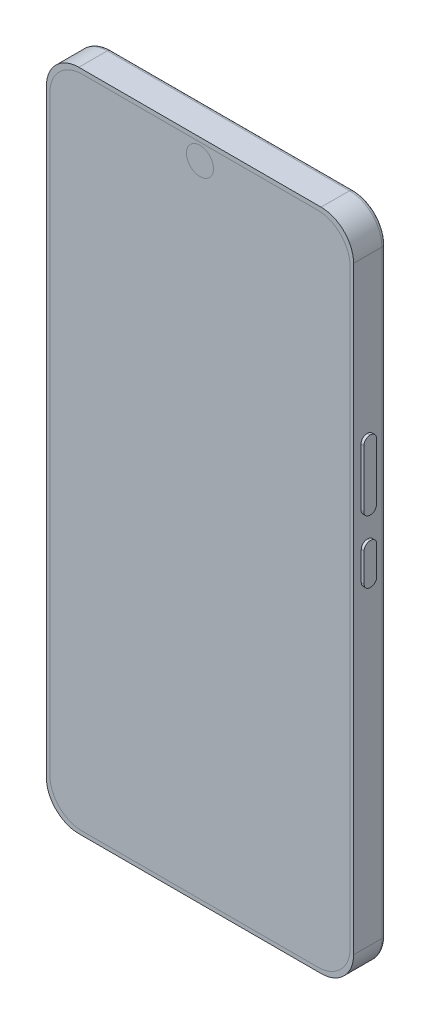
SolidWorks part; units mm, degrees
ref_plane "前视基准面" through (0, 0, 0) normal (0, 0, 1) x (1, 0, 0)
ref_plane "上视基准面" through (0, 0, 0) normal (0, 1, 0) x (1, 0, 0)
ref_plane "右视基准面" through (0, 0, 0) normal (1, 0, 0) x (0, 0, -1)
other "Configuration Table"
sketch "草图1" plane through (0, 0, 0) normal (0, 0, 1) x (1, 0, 0)
  line L1 (-62.3483, 120.7057) -> (-2.6683, 120.7057)
  line L2 (-70.3483, 112.7057) -> (-70.3483, -34.8243)
  line L3 (-62.3483, -42.8243) -> (-2.6683, -42.8243)
  line L4 (5.3317, 112.7057) -> (5.3317, -34.8243)
  arc A0 (-70.3483, -34.8243) -> (-62.3483, -42.8243) centre (-62.3483, -34.8243) ccw
  arc A1 (-2.6683, -42.8243) -> (5.3317, -34.8243) centre (-2.6683, -34.8243) ccw
  arc A2 (-2.6683, 120.7057) -> (5.3317, 112.7057) centre (-2.6683, 112.7057) cw
  arc A3 (-62.3483, 120.7057) -> (-70.3483, 112.7057) centre (-62.3483, 112.7057) ccw
  dimension "D1" = 8
extrude "凸台-拉伸2" add sketch "草图1" along normal blind 7.99
fillet "圆角4" radius 1 8 edges at (-32.5083, -42.8243, 0) (2.9886, -40.4812, 0) (5.3317, 38.9407, 0) (2.9886, 118.3625, 0) (-32.5083, 120.7057, 0) (-68.0052, 118.3625, 0) (-70.3483, 38.9407, 0) (-68.0052, -40.4812, 0)
sketch "草图2" plane through (0, 0, 7.99) normal (0, 0, 1) x (1, 0, 0)
  line L1 (-61.5125, 119.6413) -> (-3.5125, 119.6413)
  line L2 (-69.5125, 111.6413) -> (-69.5125, -33.8587)
  line L3 (-61.5125, -41.8587) -> (-3.5125, -41.8587)
  line L4 (4.4875, 111.6413) -> (4.4875, -33.8587)
  arc A0 (-69.5125, -33.8587) -> (-61.5125, -41.8587) centre (-61.5125, -33.8587) ccw
  arc A1 (-3.5125, -41.8587) -> (4.4875, -33.8587) centre (-3.5125, -33.8587) ccw
  arc A2 (-3.5125, 119.6413) -> (4.4875, 111.6413) centre (-3.5125, 111.6413) cw
  arc A3 (-61.5125, 119.6413) -> (-69.5125, 111.6413) centre (-61.5125, 111.6413) ccw
  circle A4 centre (-32.5125, 115.6413) radius 3.336
  dimension "D1" = 8
split line "分割线2"
sketch "草图6" plane through (0, 0, 0) normal (0, 0, -1) x (-1, 0, 0)
  line L0 (23.2504, 119.7057) -> (23.2504, -42.8243)
  line L1 (62.3483, 119.7057) -> (2.6683, 119.7057) construction
  line L2 (62.3483, -42.8243) -> (2.6683, -42.8243) construction
split line "分割线3"
sketch "草图7" plane through (5.3317, -15.0496, 0) normal (1, 0, 0) x (0, 0, -1)
  line L0 (-4.598, 67.2454) -> (-4.4802, 67.2454)
  line L1 (-4.6532, 89.7825) -> (-4.5354, 89.7825)
  line L2 (-6.1532, 88.2825) -> (-6.1532, 74.219)
  line L3 (-4.6532, 72.719) -> (-4.5354, 72.719)
  line L4 (-3.0354, 88.2825) -> (-3.0354, 74.219)
  line L5 (-6.098, 65.7454) -> (-6.098, 58.7454)
  line L6 (-4.598, 57.2454) -> (-4.4802, 57.2454)
  line L7 (-2.9802, 65.7454) -> (-2.9802, 58.7454)
  arc A0 (-4.5354, 72.719) -> (-3.0354, 74.219) centre (-4.5354, 74.219) ccw
  arc A1 (-6.1532, 74.219) -> (-4.6532, 72.719) centre (-4.6532, 74.219) ccw
  arc A2 (-4.5354, 89.7825) -> (-3.0354, 88.2825) centre (-4.5354, 88.2825) cw
  arc A3 (-4.6532, 89.7825) -> (-6.1532, 88.2825) centre (-4.6532, 88.2825) ccw
  arc A4 (-4.4802, 57.2454) -> (-2.9802, 58.7454) centre (-4.4802, 58.7454) ccw
  arc A5 (-6.098, 58.7454) -> (-4.598, 57.2454) centre (-4.598, 58.7454) ccw
  arc A6 (-4.4802, 67.2454) -> (-2.9802, 65.7454) centre (-4.4802, 65.7454) cw
  arc A7 (-4.598, 67.2454) -> (-6.098, 65.7454) centre (-4.598, 65.7454) ccw
  dimension "D1" = 1.5
extrude "凸台-拉伸4" add sketch "草图7" along normal blind 0.7 contours L2 A1 L3 A0 L4 A2 L1 A3 | L0 A6 L7 A4 L6 A5 L5 A7
sketch "草图8" plane through (0, -42.8243, 0) normal (0, -1, 0) x (1, 0, 0)
  line L1 (-59.1647, 6.3345) -> (-49.1647, 6.3345)
  line L2 (-60.9647, 4.5345) -> (-60.9647, 4.3535)
  line L3 (-59.1647, 2.5535) -> (-49.1647, 2.5535)
  line L4 (-47.3647, 4.5345) -> (-47.3647, 4.3535)
  arc A0 (-49.1647, 6.3345) -> (-47.3647, 4.5345) centre (-49.1647, 4.5345) cw
  arc A1 (-49.1647, 2.5535) -> (-47.3647, 4.3535) centre (-49.1647, 4.3535) ccw
  arc A2 (-60.9647, 4.3535) -> (-59.1647, 2.5535) centre (-59.1647, 4.3535) ccw
  arc A3 (-59.1647, 6.3345) -> (-60.9647, 4.5345) centre (-59.1647, 4.5345) ccw
  dimension "D1" = 1.8
split line "分割线5"
sketch "草图13" plane through (0, -42.8243, 0) normal (0, -1, 0) x (1, 0, 0)
  circle A0 centre (-59.1647, 4.4434) radius 0.9485
extrude "切除-拉伸2" cut sketch "草图13" against normal blind 1 contours A0
sketch "草图14" plane through (0, -42.8243, 0) normal (0, -1, 0) x (1, 0, 0)
  line L1 (-35.2629, 5.531) -> (-28.1557, 5.531)
  line L2 (-35.9629, 4.831) -> (-35.9629, 3.7261)
  line L3 (-35.2629, 3.0261) -> (-28.1557, 3.0261)
  line L4 (-27.4557, 4.831) -> (-27.4557, 3.7261)
  arc A0 (-28.1557, 3.0261) -> (-27.4557, 3.7261) centre (-28.1557, 3.7261) ccw
  arc A1 (-28.1557, 5.531) -> (-27.4557, 4.831) centre (-28.1557, 4.831) cw
  arc A2 (-35.9629, 3.7261) -> (-35.2629, 3.0261) centre (-35.2629, 3.7261) ccw
  arc A3 (-35.2629, 5.531) -> (-35.9629, 4.831) centre (-35.2629, 4.831) ccw
  dimension "D1" = 0.7
extrude "切除-拉伸3" cut sketch "草图14" against normal blind 1.5
sketch "草图16" plane through (0, -42.8243, 0) normal (0, -1, 0) x (-1, 0, 0)
  line L0 (16.9367, -5.4827) -> (16.7745, -5.4827)
  line L3 (17.5367, -4.8827) -> (17.5367, -3.6428)
  line L4 (19.4828, -5.4661) -> (19.3207, -5.4661)
  line L5 (20.0828, -4.8661) -> (20.0828, -3.6261)
  line L6 (19.4828, -3.0261) -> (19.3207, -3.0261)
  line L7 (18.7207, -4.8661) -> (18.7207, -3.6261)
  line L8 (16.9367, -3.0428) -> (16.7745, -3.0428)
  line L9 (16.1745, -4.8827) -> (16.1745, -3.6428)
  line L10 (14.7042, -5.4952) -> (14.542, -5.4952)
  line L11 (15.3042, -4.8952) -> (15.3042, -3.6552)
  line L12 (14.7042, -3.0552) -> (14.542, -3.0552)
  line L13 (13.942, -4.8952) -> (13.942, -3.6552)
  line L14 (-17.0763, -1.22) -> (-17.2384, -1.22)
  line L15 (-16.4763, -0.62) -> (-16.4763, 0.62)
  line L16 (-17.0763, 1.22) -> (-17.2384, 1.22)
  line L17 (-17.8384, -0.62) -> (-17.8384, 0.62)
  line L18 (12.292, -5.5002) -> (12.1299, -5.5002)
  line L19 (12.892, -4.9002) -> (12.892, -3.6602)
  line L20 (12.292, -3.0602) -> (12.1299, -3.0602)
  line L21 (11.5299, -4.9002) -> (11.5299, -3.6602)
  line L22 (9.9846, -5.4824) -> (9.8225, -5.4824)
  line L23 (10.5846, -4.8824) -> (10.5846, -3.6424)
  line L24 (9.9846, -3.0424) -> (9.8225, -3.0424)
  line L25 (9.2225, -4.8824) -> (9.2225, -3.6424)
  line L26 (7.785, -5.4824) -> (7.6228, -5.4824)
  line L27 (8.385, -4.8824) -> (8.385, -3.6424)
  line L28 (7.785, -3.0424) -> (7.6228, -3.0424)
  line L29 (7.0228, -4.8824) -> (7.0228, -3.6424)
  line L30 (40.4458, -5.5353) -> (40.2836, -5.5353)
  line L31 (41.0458, -4.9353) -> (41.0458, -3.6953)
  line L32 (40.4458, -3.0953) -> (40.2836, -3.0953)
  line L33 (39.6836, -4.9353) -> (39.6836, -3.6953)
  arc A2 (20.0828, -3.6261) -> (19.4828, -3.0261) centre (19.4828, -3.6261) ccw
  arc A3 (19.3207, -5.4661) -> (18.7207, -4.8661) centre (19.3207, -4.8661) cw
  arc A4 (19.3207, -3.0261) -> (18.7207, -3.6261) centre (19.3207, -3.6261) ccw
  arc A5 (19.4828, -5.4661) -> (20.0828, -4.8661) centre (19.4828, -4.8661) ccw
  arc A6 (17.5367, -3.6428) -> (16.9367, -3.0428) centre (16.9367, -3.6428) ccw
  arc A7 (16.7745, -5.4827) -> (16.1745, -4.8827) centre (16.7745, -4.8827) cw
  arc A8 (16.7745, -3.0428) -> (16.1745, -3.6428) centre (16.7745, -3.6428) ccw
  arc A9 (16.9367, -5.4827) -> (17.5367, -4.8827) centre (16.9367, -4.8827) ccw
  arc A10 (15.3042, -3.6552) -> (14.7042, -3.0552) centre (14.7042, -3.6552) ccw
  arc A11 (14.542, -5.4952) -> (13.942, -4.8952) centre (14.542, -4.8952) cw
  arc A12 (14.542, -3.0552) -> (13.942, -3.6552) centre (14.542, -3.6552) ccw
  arc A13 (14.7042, -5.4952) -> (15.3042, -4.8952) centre (14.7042, -4.8952) ccw
  arc A14 (-16.4763, 0.62) -> (-17.0763, 1.22) centre (-17.0763, 0.62) ccw
  arc A15 (-17.2384, -1.22) -> (-17.8384, -0.62) centre (-17.2384, -0.62) cw
  arc A16 (-17.2384, 1.22) -> (-17.8384, 0.62) centre (-17.2384, 0.62) ccw
  arc A17 (-17.0763, -1.22) -> (-16.4763, -0.62) centre (-17.0763, -0.62) ccw
  arc A18 (12.892, -3.6602) -> (12.292, -3.0602) centre (12.292, -3.6602) ccw
  arc A19 (12.1299, -5.5002) -> (11.5299, -4.9002) centre (12.1299, -4.9002) cw
  arc A20 (12.1299, -3.0602) -> (11.5299, -3.6602) centre (12.1299, -3.6602) ccw
  arc A21 (12.292, -5.5002) -> (12.892, -4.9002) centre (12.292, -4.9002) ccw
  arc A22 (10.5846, -3.6424) -> (9.9846, -3.0424) centre (9.9846, -3.6424) ccw
  arc A23 (9.8225, -5.4824) -> (9.2225, -4.8824) centre (9.8225, -4.8824) cw
  arc A24 (9.8225, -3.0424) -> (9.2225, -3.6424) centre (9.8225, -3.6424) ccw
  arc A25 (9.9846, -5.4824) -> (10.5846, -4.8824) centre (9.9846, -4.8824) ccw
  arc A26 (8.385, -3.6424) -> (7.785, -3.0424) centre (7.785, -3.6424) ccw
  arc A27 (7.6228, -5.4824) -> (7.0228, -4.8824) centre (7.6228, -4.8824) cw
  arc A28 (7.6228, -3.0424) -> (7.0228, -3.6424) centre (7.6228, -3.6424) ccw
  arc A29 (7.785, -5.4824) -> (8.385, -4.8824) centre (7.785, -4.8824) ccw
  arc A30 (41.0458, -3.6953) -> (40.4458, -3.0953) centre (40.4458, -3.6953) ccw
  arc A31 (40.2836, -5.5353) -> (39.6836, -4.9353) centre (40.2836, -4.9353) cw
  arc A32 (40.2836, -3.0953) -> (39.6836, -3.6953) centre (40.2836, -3.6953) ccw
  arc A33 (40.4458, -5.5353) -> (41.0458, -4.9353) centre (40.4458, -4.9353) ccw
  point P23 (18.7207, -3.0261)
  point P26 (20.0828, -5.4661)
  dimension "D1" = 0.6
extrude "切除-拉伸4" cut sketch "草图16" against normal blind 1.5
sketch "草图18" plane through (0, 0, 0) normal (0, 0, -1) x (-1, 0, 0)
  line L3 (25.0125, 102.093) -> (29.0125, 102.093)
  line L4 (24.949, 111.7027) -> (28.949, 111.7027)
  line L5 (24.449, 111.2027) -> (24.449, 107.2027)
  line L6 (24.949, 106.7027) -> (28.949, 106.7027)
  line L7 (29.449, 111.2027) -> (29.449, 107.2027)
  line L8 (24.5125, 101.593) -> (24.5125, 97.593)
  line L9 (25.0125, 97.093) -> (29.0125, 97.093)
  line L10 (29.5125, 101.593) -> (29.5125, 97.593)
  arc A0 (24.449, 107.2027) -> (24.949, 106.7027) centre (24.949, 107.2027) ccw
  arc A1 (28.949, 106.7027) -> (29.449, 107.2027) centre (28.949, 107.2027) ccw
  arc A2 (28.949, 111.7027) -> (29.449, 111.2027) centre (28.949, 111.2027) cw
  arc A3 (24.949, 111.7027) -> (24.449, 111.2027) centre (24.949, 111.2027) ccw
  arc A4 (24.5125, 97.593) -> (25.0125, 97.093) centre (25.0125, 97.593) ccw
  arc A5 (29.0125, 97.093) -> (29.5125, 97.593) centre (29.0125, 97.593) ccw
  arc A6 (29.0125, 102.093) -> (29.5125, 101.593) centre (29.0125, 101.593) cw
  arc A7 (25.0125, 102.093) -> (24.5125, 101.593) centre (25.0125, 101.593) ccw
  dimension "D1" = 0.5
extrude "切除-拉伸6" cut sketch "草图18" against normal blind 0.2
